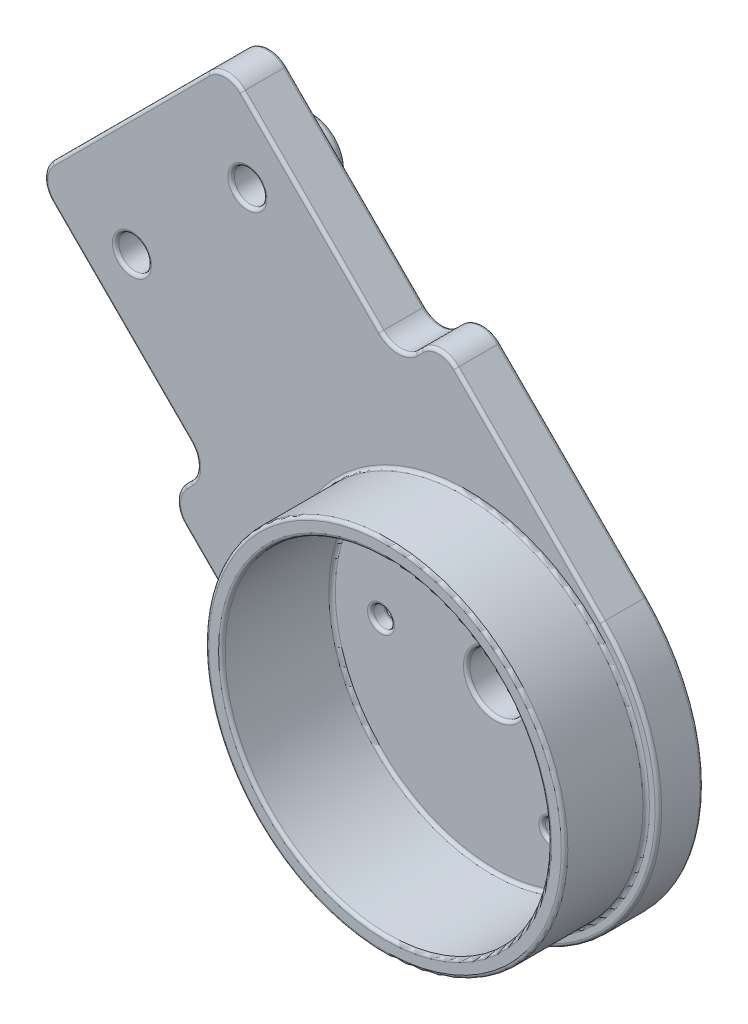
SolidWorks part; units mm, degrees
ref_plane "Front Plane" through (0, 0, 0) normal (0, 0, 1) x (1, 0, 0)
ref_plane "Top Plane" through (0, 0, 0) normal (0, 1, 0) x (1, 0, 0)
ref_plane "Right Plane" through (0, 0, 0) normal (1, 0, 0) x (0, 0, -1)
sketch "Sketch1" plane through (0, 0, 0) normal (0, 0, 1) x (1, 0, 0)
  line L0 (-100, 0) -> (100, 0) construction
  line L1 (-100, 0) -> (0, 100) construction
  line L2 (0, 100) -> (100, 0) construction
  line L3 (0, 0) -> (-50, 50) construction
  line L4 (-40, 60) -> (40, 60) construction
  line L5 (0, 100) -> (0, 60) construction
  circle A0 centre (-100, 0) radius 20
  circle A1 centre (0, 0) radius 20
  circle A2 centre (100, 0) radius 20
  point P2 (0, 0)
  dimension "D5" = 40
  dimension "D1" = 200
  dimension "D2" = 90
  dimension "D3" = 90
  dimension "D4" = 80
sketch "Sketch2" plane through (0, 0, 0) normal (0, 0, 1) x (1, 0, 0)
  line L0 (-56.5165, 43.4835) -> (-40, 60) construction
  line L1 (-100, 0) -> (0, 100) construction
  line L2 (-40, 60) -> (40, 60) construction
  line L3 (40, 60) -> (86.565, 13.435) construction
  line L4 (0, 100) -> (100, 0) construction
  line L5 (-49.4454, 36.4124) -> (-35.8579, 50)
  line L6 (-35.8579, 50) -> (35.8579, 50)
  line L7 (35.8579, 50) -> (79.4939, 6.364)
  line L8 (-63.5876, 50.5546) -> (-44.1421, 70)
  line L9 (-44.1421, 70) -> (44.1421, 70)
  line L10 (44.1421, 70) -> (93.636, 20.5061)
  line L11 (-63.5876, 50.5546) -> (-49.4454, 36.4124)
  line L12 (93.636, 20.5061) -> (79.4939, 6.364)
  line L13 (90.9809, 17.8509) -> (104.534, 4.6576)
  line L14 (82.1491, 9.0191) -> (95.3424, -4.534)
  line L15 (90.1005, 24.0416) -> (75.9584, 9.8995)
  line L16 (0, 100) -> (0, 60) construction
  line L17 (-6, 70) -> (-3.4532, 85.4203)
  line L18 (6, 70) -> (3.4532, 85.4203)
  circle A0 centre (100, 0) radius 3.5
  circle A1 centre (100, 0) radius 10 construction
  arc A2 (95.3424, -4.534) -> (104.534, 4.6576) centre (100, 0) ccw
  circle A3 centre (100, 0) radius 0.5
  circle A4 centre (100, 0) radius 20 construction
  circle A5 centre (100, 0) radius 6.5 construction
  circle A6 centre (79.4939, 13.435) radius 1
  circle A7 centre (86.565, 20.5061) radius 1
  circle A8 centre (0, 60) radius 1.5
  circle A9 centre (0, 84.85) radius 1.5
  arc A10 (3.4532, 85.4203) -> (-3.4532, 85.4203) centre (0, 84.85) ccw
  circle A11 centre (0, 84.85) radius 3.5 construction
  circle A12 centre (-50, 50) radius 1.5
  dimension "D4" = 20
  dimension "D5" = 7
  dimension "D10" = 2
  dimension "D13" = 3
  dimension "D18" = 3
  dimension "D3" = 27.5
  dimension "D8" = 19
  dimension "D9" = 5
  dimension "D11" = 5
  dimension "D12" = 5
  dimension "D14" = 14.85
  dimension "D16" = 6
  dimension "D17" = 6
  dimension "D1" = 10
  dimension "D2" = 10
  dimension "D6" = 3
  dimension "D7" = 3
  dimension "D15" = 2
sketch "Sketch3" plane through (0, 0, 0) normal (0, 0, 1) x (1, 0, 0)
  line L1 (-100, 0) -> (0, 100) construction
  line L2 (-86.565, 13.435) -> (-50, 50) construction
  line L3 (-50, 50) -> (-13.435, 13.435) construction
  line L4 (0, 0) -> (-50, 50) construction
  line L5 (-93.636, 20.5061) -> (-50, 64.1421)
  line L6 (-50, 64.1421) -> (-6.364, 20.5061)
  line L7 (-79.4939, 6.364) -> (-50, 35.8579)
  line L8 (-50, 35.8579) -> (-20.5061, 6.364)
  line L9 (-93.636, 20.5061) -> (-50, 64.1421) construction
  line L10 (-79.4939, 6.364) -> (-50, 35.8579) construction
  line L11 (-93.636, 20.5061) -> (-79.4939, 6.364)
  line L12 (-6.364, 20.5061) -> (-20.5061, 6.364)
  line L13 (-104.5962, 4.5962) -> (-91.2218, 17.9706)
  line L14 (-95.4038, -4.5962) -> (-82.0294, 8.7782)
  line L15 (-17.9706, 8.7782) -> (-4.5962, -4.5962)
  line L16 (-8.7782, 17.9706) -> (4.5962, 4.5962)
  line L17 (-90.1005, 24.0416) -> (-75.9584, 9.8995) construction
  line L18 (-24.0416, 9.8995) -> (-9.8995, 24.0416) construction
  circle A0 centre (-100, 0) radius 10 construction
  circle A1 centre (-100, 0) radius 3.5
  circle A2 centre (0, 0) radius 3.5
  circle A3 centre (0, 0) radius 10 construction
  arc A4 (-4.5962, -4.5962) -> (4.5962, 4.5962) centre (0, 0) ccw
  arc A5 (-104.5962, 4.5962) -> (-95.4038, -4.5962) centre (-100, 0) ccw
  circle A6 centre (-86.565, 20.5061) radius 1
  circle A7 centre (-100, 0) radius 20 construction
  circle A8 centre (0, 0) radius 20 construction
  circle A9 centre (-100, 0) radius 6.5 construction
  circle A10 centre (0, 0) radius 6.5 construction
  circle A11 centre (-79.4939, 13.435) radius 1
  circle A12 centre (-20.5061, 13.435) radius 1
  circle A13 centre (-13.435, 20.5061) radius 1
  circle A14 centre (-50, 50) radius 1.5 construction
  circle A15 centre (-50, 50) radius 1.5
  dimension "D1" = 20
  dimension "D2" = 7
  dimension "D8" = 2
  dimension "D6" = 19
  dimension "D7" = 19
  dimension "D9" = 5
  dimension "D10" = 5
  dimension "D11" = 5
  dimension "D12" = 5
  dimension "D13" = 5
  dimension "D14" = 5
  dimension "D3" = 3
  dimension "D4" = 10
  dimension "D5" = 10
sketch "Sketch4" plane through (0, 0, 0) normal (0, 0, 1) x (1, 0, 0)
  line L0 (-57.5, 94.8011) -> (57.5, 94.8011)
  line L1 (57.5, 94.8011) -> (57.5, 84.8011)
  line L2 (57.5, 84.8011) -> (44.1421, 70)
  line L3 (44.1421, 70) -> (-44.1421, 70)
  line L4 (-44.1421, 70) -> (-57.5, 84.8011)
  line L5 (-57.5, 84.8011) -> (-57.5, 94.8011)
  line L6 (4, 60) -> (4, 70)
  line L7 (-4, 60) -> (-4, 70)
  line L9 (-22.5, 86.3011) -> (22.5, 86.3011) construction
  line L10 (-22.5, 90.8011) -> (22.5, 90.8011)
  line L11 (-22.5, 81.8011) -> (22.5, 81.8011)
  circle A0 centre (0, 60) radius 1.5 construction
  circle A1 centre (0, 60) radius 1.5
  arc A2 (-4, 60) -> (4, 60) centre (0, 60) ccw
  circle A3 centre (0, 60) radius 4 construction
  arc A4 (-22.5, 90.8011) -> (-22.5, 81.8011) centre (-22.5, 86.3011) ccw
  arc A5 (22.5, 81.8011) -> (22.5, 90.8011) centre (22.5, 86.3011) ccw
  point P19 (0, 86.3011)
  dimension "D1" = 115
  dimension "D2" = 10
  dimension "D3" = 2.5
  dimension "D4" = 45
  dimension "D5" = 9
  dimension "D6" = 4
sketch "Sketch6" plane through (0, 0, 0) normal (0, 0, 1) x (1, 0, 0)
  line L0 (73.5224, 14.8103) -> (85.1897, 26.4776)
  line L1 (90.1005, 24.0416) -> (75.9584, 9.8995) construction
  line L2 (0, 100) -> (100, 0) construction
  line L3 (73.5224, 14.8103) -> (84.129, 4.2037)
  line L4 (84.129, 4.2037) -> (81.6542, 1.7288)
  line L5 (81.6542, 1.7288) -> (91.6915, -8.3085)
  line L6 (100, 0) -> (92.184, 7.816) construction
  line L7 (98.2712, 18.3458) -> (108.3085, 8.3085)
  line L8 (95.7963, 15.871) -> (98.2712, 18.3458)
  line L9 (85.1897, 26.4776) -> (95.7963, 15.871)
  circle A0 centre (100, 0) radius 10 construction
  circle A1 centre (100, 0) radius 10
  arc A2 (91.6915, -8.3085) -> (108.3085, 8.3085) centre (100, 0) ccw
  circle A3 centre (100, 0) radius 11.75 construction
  circle A4 centre (79.4939, 13.435) radius 1 construction
  circle A5 centre (86.565, 20.5061) radius 1 construction
  circle A6 centre (79.4939, 13.435) radius 1
  circle A7 centre (86.565, 20.5061) radius 1
  point P9 (79.3561, 20.6439)
  dimension "D2" = 16.5
  dimension "D3" = 14.1949
  dimension "D4" = 15
  dimension "D1" = 1.75
extrude "Boss-Extrude1" add sketch "Sketch6" against normal blind 2.75
sketch "Sketch7" plane through (0, 0, -2.75) normal (0, 0, -1) x (-1, 0, 0)
  circle A0 centre (-100, 0) radius 10 construction
  circle A1 centre (-100, 0) radius 10
extrude "Boss-Extrude2" add sketch "Sketch7" against normal blind 1
sketch "Sketch8" plane through (0, 0, 0) normal (0, 0, 1) x (1, 0, 0)
  circle A0 centre (100, 0) radius 10 construction
  circle A1 centre (100, 0) radius 10
  circle A4 centre (100, 0) radius 11
  circle A5 centre (100, 0) radius 11
  dimension "D1" = 1
extrude "Boss-Extrude3" add sketch "Sketch8" along normal blind 5
sketch "Sketch9" plane through (0, 0, -2.75) normal (0, 0, -1) x (-1, 0, 0)
  circle A0 centre (-79.4939, 13.435) radius 1 construction
  circle A1 centre (-86.565, 20.5061) radius 1 construction
  circle A2 centre (-79.4939, 13.435) radius 1
  circle A3 centre (-86.565, 20.5061) radius 1
  circle A4 centre (-86.565, 20.5061) radius 2
  circle A5 centre (-79.4939, 13.435) radius 2
  dimension "D1" = 1
extrude "Boss-Extrude4" add sketch "Sketch9" along normal blind 1.25
fillet "Fillet1" radius 1.5 6 edges at (84.129, 4.2037, -1.375) (81.6542, 1.7288, -1.375) (98.2712, 18.3458, -1.375) (95.7963, 15.871, -1.375) (85.1897, 26.4776, -1.375) (73.5224, 14.8103, -1.375)
sketch "Sketch10" plane through (0, 0, -2.75) normal (0, 0, -1) x (-1, 0, 0)
  circle A0 centre (-100, 0) radius 1.75
  dimension "D1" = 3.5
extrude "Cut-Extrude1" cut sketch "Sketch10" against normal blind 1.25
sketch "Sketch11" plane through (0, 0, -2.75) normal (0, 0, -1) x (-1, 0, 0)
  circle A0 centre (-100, 0) radius 1.75 construction
  circle A1 centre (-100, 0) radius 1.75
  circle A2 centre (-100, 0) radius 3.45
  dimension "D1" = 6.9
extrude "Boss-Extrude5" add sketch "Sketch11" along normal blind 4.25
sketch "Sketch12" plane through (0, 0, -2.75) normal (0, 0, -1) x (-1, 0, 0)
  line L0 (-100, 0) -> (-93, 0) construction
  circle A0 centre (-93, 0) radius 0.625
  circle A1 centre (-103.5, -6.0622) radius 0.625
  circle A2 centre (-103.5, 6.0622) radius 0.625
  point P12 (-100, 0)
  dimension "D1" = 1.25
  dimension "D2" = 7
  dimension "D3" = 3
extrude "Cut-Extrude2" cut sketch "Sketch12" against normal blind 4.25
fillet "Fillet3" radius 0.2 50 edges at (102.875, 6.0622, -2.75) (102.875, -6.0622, -2.75) (92.375, 0, -2.75) (102.875, 6.0622, -1.75) (102.875, -6.0622, -1.75) (92.375, 0, -1.75) (98.25, 0, -7) (96.55, 0, -7) (98.25, 0, -1.75) (77.4939, 13.435, -4) (85.565, 20.5061, -4) (84.565, 20.5061, -4) (110, 0, 5) (111, 0, 0) (111, 0, 5) (87.565, 20.5061, 0) (80.4939, 13.435, 0) (78.8257, 9.507, 0) (82.8916, 2.9663, 0) (87.2032, -3.8202, 0) (108.3085, -8.3085, 0) (103.8202, 12.7968, 0) (97.0337, 17.1084, 0) (90.493, 21.1743, 0) (79.3561, 20.6439, 0) (78.8257, 9.507, -2.75) (82.8916, 2.9663, -2.75) (87.2032, -3.8202, -2.75) (108.3085, -8.3085, -2.75) (103.8202, 12.7968, -2.75) (97.0337, 17.1084, -2.75) (90.493, 21.1743, -2.75) (79.3561, 20.6439, -2.75) (90, 0, -1.75) (88.565, 20.5061, -2.75) (81.4939, 13.435, -2.75) (74.1438, 14.8103, 0) (85.1897, 25.8562, 0) (98.2712, 17.7245, 0) (82.2755, 1.7288, 0) (74.1438, 14.8103, -2.75) (85.1897, 25.8562, -2.75) (98.2712, 17.7245, -2.75) (82.2755, 1.7288, -2.75) (83.5077, 4.2037, 0) (83.5077, 4.2037, -2.75) (95.7963, 16.4923, 0) (95.7963, 16.4923, -2.75) (103.45, 0, -2.75) (78.4939, 13.435, -4)
